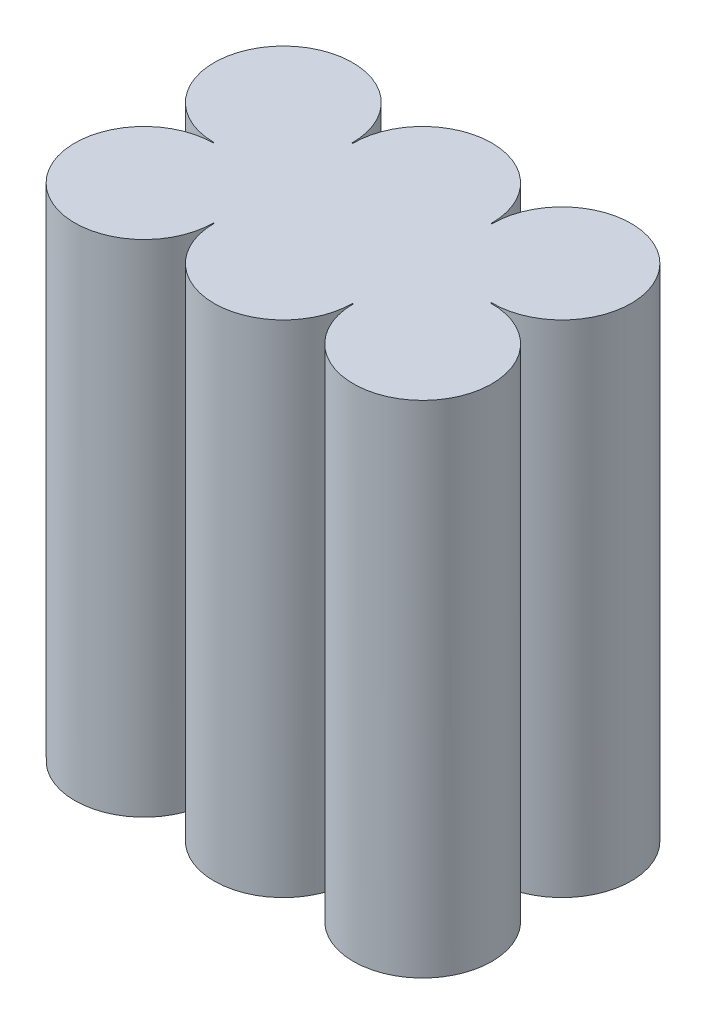
SolidWorks part; units mm, degrees
ref_plane "Alzado" through (0, 0, 0) normal (0, 0, 1) x (1, 0, 0)
ref_plane "Planta" through (0, 0, 0) normal (0, 1, 0) x (1, 0, 0)
ref_plane "Vista lateral" through (0, 0, 0) normal (1, 0, 0) x (0, 0, -1)
sketch "Croquis1" plane through (0, 0, 0) normal (0, 1, 0) x (1, 0, 0)
  circle A0 centre (0, 0) radius 9
  dimension "D1" = 18
extrude "Saliente-Extruir1" add sketch "Croquis1" along normal blind 65
sketch "Croquis2" plane through (0, 65, 0) normal (0, 1, 0) x (1, 0, 0)
  line L1 (0, 0) -> (36, 0)
  line L2 (0, 0) -> (0, 18)
  line L3 (0, 18) -> (36, 18)
  line L4 (36, 0) -> (36, 18)
  point P5 (38.1751, 22.7971)
  dimension "D1" = 36
  dimension "D2" = 18
extrude "Saliente-Extruir2" add sketch "Croquis2" against normal blind 10
pattern_linear "MatrizL1" count 3 spacing 18.1 along (1, 0, 0) count 2 spacing 18.1 along (0, 0, -1) of "Saliente-Extruir1"
